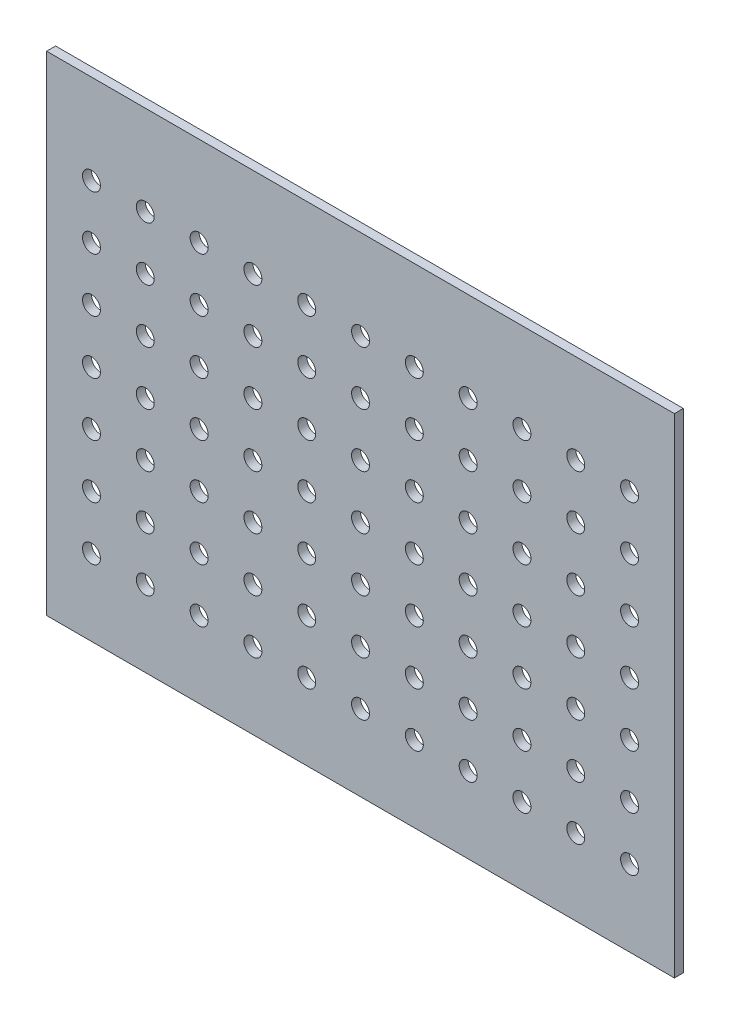
SolidWorks part; units mm, degrees
ref_plane "Alzado" through (0, 0, 0) normal (0, 0, 1) x (1, 0, 0)
ref_plane "Planta" through (0, 0, 0) normal (0, 1, 0) x (1, 0, 0)
ref_plane "Vista lateral" through (0, 0, 0) normal (1, 0, 0) x (0, 0, -1)
sketch "Croquis1" plane through (0, 0, 0) normal (0, 0, 1) x (1, 0, 0)
  line L1 (-357.8007, 266.8557) -> (342.1993, 266.8557)
  line L2 (-357.8007, 266.8557) -> (-357.8007, -278.1443)
  line L3 (-357.8007, -278.1443) -> (342.1993, -278.1443)
  line L4 (342.1993, 266.8557) -> (342.1993, -278.1443)
  dimension "D1" = 700
  dimension "D2" = 545
extrude "Saliente-Extruir1" add sketch "Croquis1" along normal blind 10
sketch "Croquis2" plane through (0, 0, 10) normal (0, 0, 1) x (1, 0, 0)
  line L1 (-357.8007, 266.8557) -> (-357.8007, -278.1443) construction
  line L2 (342.1993, 266.8557) -> (-357.8007, 266.8557) construction
  circle A0 centre (-307.8007, 166.8557) radius 10
  dimension "D1" = 50
  dimension "D2" = 100
extrude "Cortar-Extruir1" cut sketch "Croquis2" against normal through all
pattern_linear "MatrizL1" count 11 spacing 60 along (1, 0, 0) count 7 spacing 60 along (0, -1, 0) of "Cortar-Extruir1"
